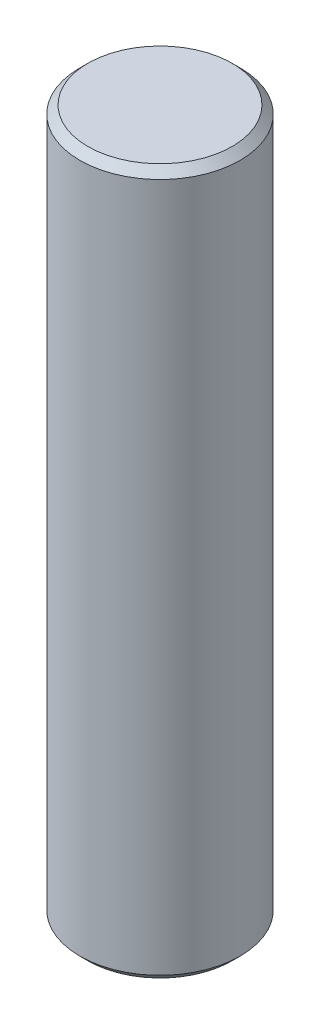
SolidWorks part; units mm, degrees
material "AISI 316 Annealed Stainless Steel Bar (SS)"
ref_plane "Front Plane" through (0, 0, 0) normal (0, 0, 1) x (1, 0, 0)
ref_plane "Top Plane" through (0, 0, 0) normal (0, 1, 0) x (1, 0, 0)
ref_plane "Right Plane" through (0, 0, 0) normal (1, 0, 0) x (0, 0, -1)
sketch "Sketch1" plane through (0, 0, 0) normal (0, 1, 0) x (1, 0, 0)
  circle A0 centre (0, 0) radius 2.5
  dimension "D1" = 5
extrude "Boss-Extrude1" add sketch "Sketch1" along normal mid plane 22
chamfer "Chamfer1" distance 0.25 angle 45 2 edges at (0, -11, 2.5) (0, 11, 2.5)
